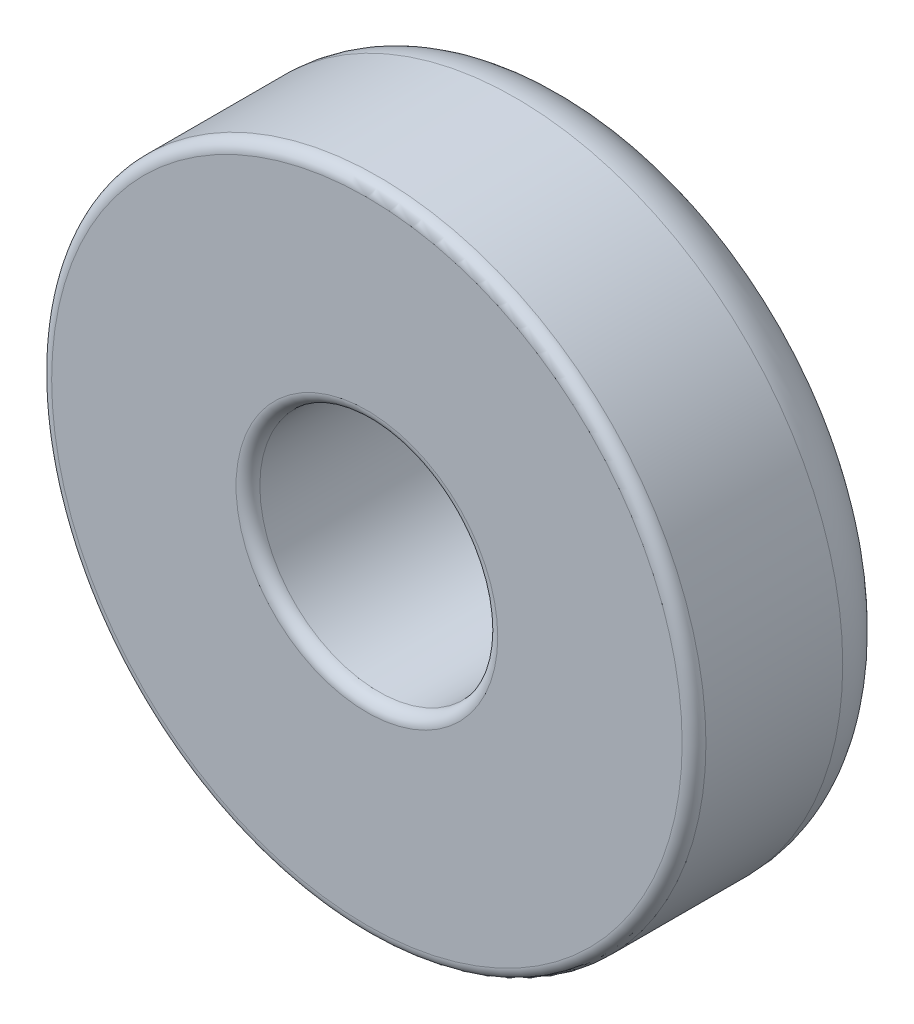
SolidWorks part; units mm, degrees
ref_plane "Front Plane" through (0, 0, 0) normal (0, 0, 1) x (1, 0, 0)
ref_plane "Top Plane" through (0, 0, 0) normal (0, 1, 0) x (1, 0, 0)
ref_plane "Right Plane" through (0, 0, 0) normal (1, 0, 0) x (0, 0, -1)
sketch "Sketch1" plane through (0, 0, 0) normal (0, 0, 1) x (1, 0, 0)
  circle A0 centre (0, 0.1009) radius 1
  dimension "D1" = 2
extrude "Extrude-Thin1" add sketch "Sketch1" along normal blind 1.75 thin
fillet "Fillet1" radius 0.5 1 edges at (2.75, 0.1009, 0)
fillet "Fillet2" radius 0.1 3 edges at (1, 0.1009, 1.75) (2.75, 0.1009, 1.75) (1, 0.1009, 0)
